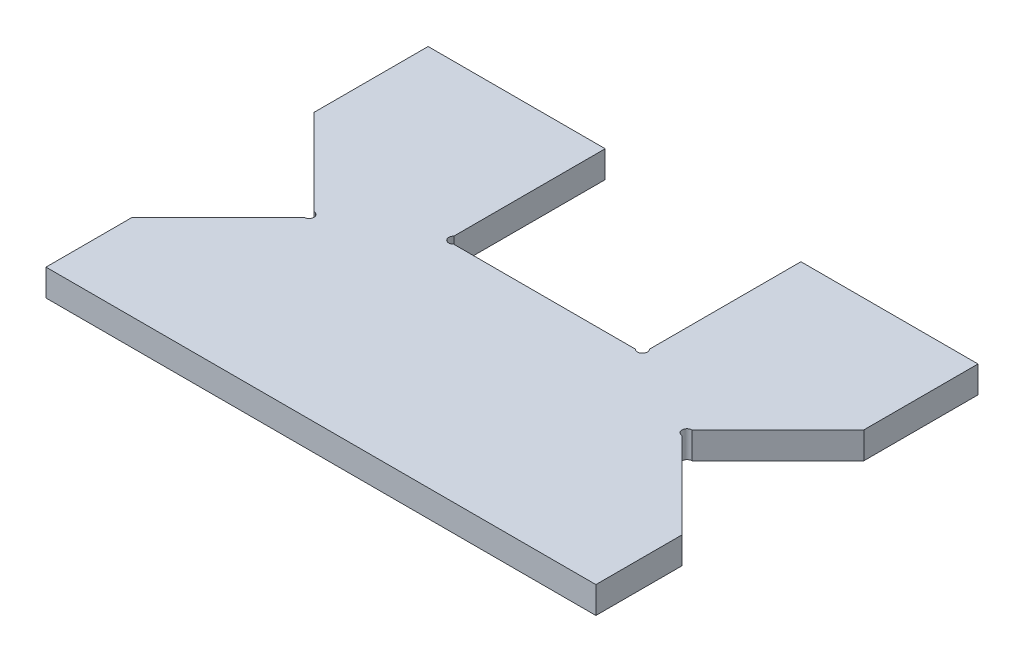
SolidWorks part; units mm, degrees
material "Pine"
ref_plane "Front Plane" through (0, 0, 0) normal (0, 0, 1) x (1, 0, 0)
ref_plane "Top Plane" through (0, 0, 0) normal (0, 1, 0) x (1, 0, 0)
ref_plane "Right Plane" through (0, 0, 0) normal (1, 0, 0) x (0, 0, -1)
sketch "Sketch1" plane through (0, 0, 0) normal (0, 1, 0) x (1, 0, 0)
  line L0 (-187.325, -558.8) -> (187.325, -558.8)
  line L1 (66.675, -107.95) -> (-66.675, -107.95)
  line L2 (66.675, -107.95) -> (66.675, 0)
  line L3 (66.675, 0) -> (-66.675, 0) construction
  line L4 (-66.675, -107.95) -> (-66.675, 0)
  line L5 (0, 0) -> (0, -107.95) construction
  line L6 (66.675, -53.975) -> (-66.675, -53.975) construction
  line L7 (-187.325, -558.8) -> (-187.325, 0)
  line L8 (-187.325, 0) -> (-66.675, 0)
  line L9 (187.325, -558.8) -> (187.325, 0)
  line L10 (187.325, 0) -> (66.675, 0)
  point P0 (0, -53.975)
  point P8 (0, -558.8)
  dimension "D1" = 107.95
  dimension "D2" = 133.35
  dimension "D3" = 450.85
  dimension "D4" = 374.65
extrude "Boss-Extrude1" add sketch "Sketch1" along normal blind 18.2562
sketch "Sketch2" plane through (0, 18.2562, 0) normal (0, 1, 0) x (1, 0, 0)
  line L0 (-187.325, -201.6125) -> (-125.4125, -139.7)
  line L1 (-187.325, 0) -> (-187.325, -558.8) construction
  line L2 (-125.4125, -139.7) -> (125.4125, -139.7) construction
  line L3 (125.4125, -139.7) -> (187.325, -201.6125)
  line L4 (187.325, -558.8) -> (187.325, 0) construction
  line L6 (-125.4125, -139.7) -> (-187.325, -77.7875)
  line L7 (-187.325, -77.7875) -> (-187.325, -201.6125)
  line L8 (125.4125, -139.7) -> (187.325, -77.7875)
  line L9 (187.325, -77.7875) -> (187.325, -201.6125)
  line L10 (-66.675, 0) -> (-187.325, 0) construction
  point P8 (0, -139.7)
  dimension "D1" = 77.7875
  dimension "D2" = 139.7
  dimension "D3" = 45
  dimension "D4" = 201.6125
extrude "Cut-Extrude1" cut sketch "Sketch2" against normal through all
hole_wizard "1/4 Clearance Hole1" positions "Sketch3" profile "Sketch4" hole size "1/4" standard "ANSI Inch" end condition up to next
sketch "Sketch3" plane through (0, 18.2562, 0) normal (0, 1, 0) x (1, 0, 0)
  line L3 (-128.7854, -139.7053) -> (128.7854, -139.7053) construction
  line L14 (-64.2938, -105.5687) -> (64.2938, -105.5687) construction
  line L15 (-125.4125, -139.7) -> (-187.325, -77.7875) construction
  line L16 (-187.325, -201.6125) -> (-125.4125, -139.7) construction
  line L18 (66.675, -107.95) -> (-66.675, -107.95) construction
  line L19 (-66.675, -107.95) -> (-66.675, 0) construction
  circle A0 centre (-128.7854, -139.7053) radius 3.3782 construction
  circle A1 centre (-64.2938, -105.5687) radius 3.3782 construction
  point P13 (-64.2938, -105.5687)
  point P15 (64.2938, -105.5687)
  point P17 (-128.7854, -139.7053)
  point P19 (128.7854, -139.7053)
  point P39 (0, -139.7053)
  point P73 (0, -105.5687)
  point P74 (0, 0)
  point P79 (0, 0)
  point P80 (0, 0)
  point P81 (0, 0)
  point P82 (-62.8336, -107.95)
  point P85 (-63.4577, -107.95)
  point P88 (0, 0)
  point P89 (0, 0)
  dimension "D1" = 6.7564
  dimension "D2" = 2.3887
  dimension "D3" = 2.3813
  dimension "D4" = 2.3813
  dimension "D5" = 2.3813
sketch "Sketch4" plane through (-64.2938, 18.2562, 105.5687) normal (1, 0, 0) x (0, 0, 1)
  line L0 (0, 0) -> (0, 18.2562)
  line L1 (0, 18.2562) -> (3.3782, 18.2562)
  line L2 (3.3782, 18.2562) -> (3.3782, 0)
  line L5 (3.3782, 0) -> (0, 0)
  line L11 (0, -6.35) -> (0, 107.95) construction
  dimension "Thru Hole Dia." = 6.7564
  dimension "Thru Hole Depth" = 18.2562
sketch "Sketch5" plane through (0, 18.2562, 0) normal (0, 1, 0) x (1, 0, 0)
  line L0 (187.325, -558.8) -> (187.325, -201.6125) construction
  line L1 (-187.325, -558.8) -> (187.325, -558.8)
  line L2 (-187.325, -558.8) -> (-187.325, -260.35)
  line L3 (-187.325, -260.35) -> (187.325, -260.35)
  line L4 (187.325, -558.8) -> (187.325, -260.35)
  line L5 (-187.325, -255.494) -> (-39.781, -107.95) construction
  line L6 (-187.325, -201.6125) -> (-187.325, -558.8) construction
  line L7 (61.8975, -107.95) -> (-61.8975, -107.95) construction
  line L8 (-187.325, -201.6125) -> (-128.796, -143.0835) construction
  line L9 (187.325, 0) -> (66.675, 0) construction
  dimension "D1" = 38.1
  dimension "D2" = 298.45
  dimension "D3" = 260.35
extrude "Cut-Extrude2" cut sketch "Sketch5" against normal through all
